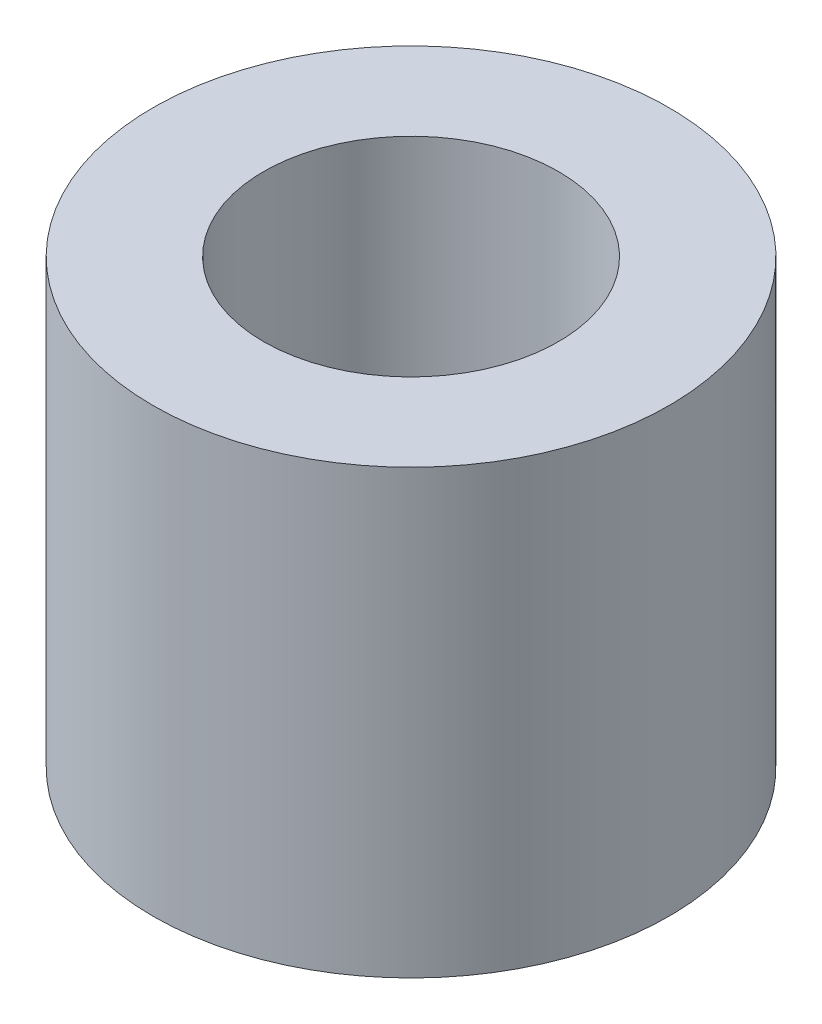
SolidWorks part; units mm, degrees
ref_plane "Спереди" through (0, 0, 0) normal (0, 0, 1) x (1, 0, 0)
ref_plane "Сверху" through (0, 0, 0) normal (0, 1, 0) x (1, 0, 0)
ref_plane "Справа" through (0, 0, 0) normal (1, 0, 0) x (0, 0, -1)
sketch "Эскиз1" plane through (0, 0, 0) normal (0, 1, 0) x (1, 0, 0)
  circle A0 centre (0, 0) radius 2
  circle A1 centre (0, 0) radius 3.5
  dimension "D1" = 4
  dimension "D2" = 7
extrude "Бобышка-Вытянуть1" add sketch "Эскиз1" along normal blind 6
